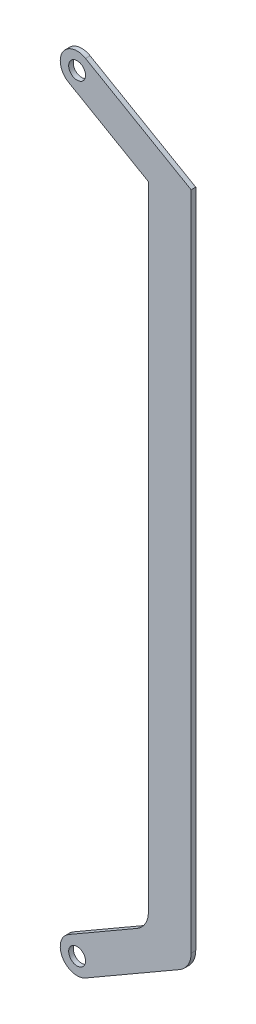
SolidWorks part; units mm, degrees
ref_plane "前视基准面" through (0, 0, 0) normal (0, 0, 1) x (1, 0, 0)
ref_plane "上视基准面" through (0, 0, 0) normal (0, 1, 0) x (1, 0, 0)
ref_plane "右视基准面" through (0, 0, 0) normal (1, 0, 0) x (0, 0, -1)
sketch "草图1" plane through (0, 0, 0) normal (0, 0, 1) x (1, 0, 0)
  line L261 (324.2897, 18.881) -> (324.2897, 433.0448)
  line L264 (296.4149, 436.4367) -> (296.4149, 24.1495)
  line L265 (324.2897, 433.0448) -> (324.2897, 18.881) construction
  line L266 (324.2897, 18.881) -> (249.9534, -24.0371) construction
  line L267 (244.4534, -14.5108) -> (255.4534, -33.5633) construction
  line L274 (244.4534, -14.5108) -> (288.9149, 11.1591)
  line L276 (316.7897, 1.8492) -> (255.4534, -33.5633)
  line L277 (324.2897, 14.8396) -> (324.2897, 18.881)
  line L278 (249.9534, 225.9629) -> (230.3036, 225.9629) construction
  line L279 (244.4534, 466.4367) -> (296.4149, 436.4367)
  line L280 (324.2897, 445.7465) -> (324.2897, 433.0448)
  line L281 (324.2897, 445.7465) -> (255.4534, 485.4892)
  circle A28 centre (249.9534, -24.0371) radius 5.5
  circle A30 centre (249.9534, 475.9629) radius 5.5
  circle A31 centre (249.9534, 475.9629) radius 11 construction
  circle A32 centre (249.9534, -24.0371) radius 11 construction
  arc A33 (255.4534, -33.5633) -> (244.4534, -14.5108) centre (249.9534, -24.0371) cw
  arc A34 (255.4534, 485.4892) -> (244.4534, 466.4367) centre (249.9534, 475.9629) ccw
  arc A35 (288.9149, 11.1591) -> (296.4149, 24.1495) centre (281.4149, 24.1495) ccw
  arc A36 (316.7897, 1.8492) -> (324.2897, 14.8396) centre (309.2897, 14.8396) ccw
  point P23 (296.4149, 15.4892)
  point P26 (324.2897, 6.1793)
  dimension "D1" = 15
  dimension "D2" = 15
extrude "凸台-拉伸1" add sketch "草图1" along normal blind 3
